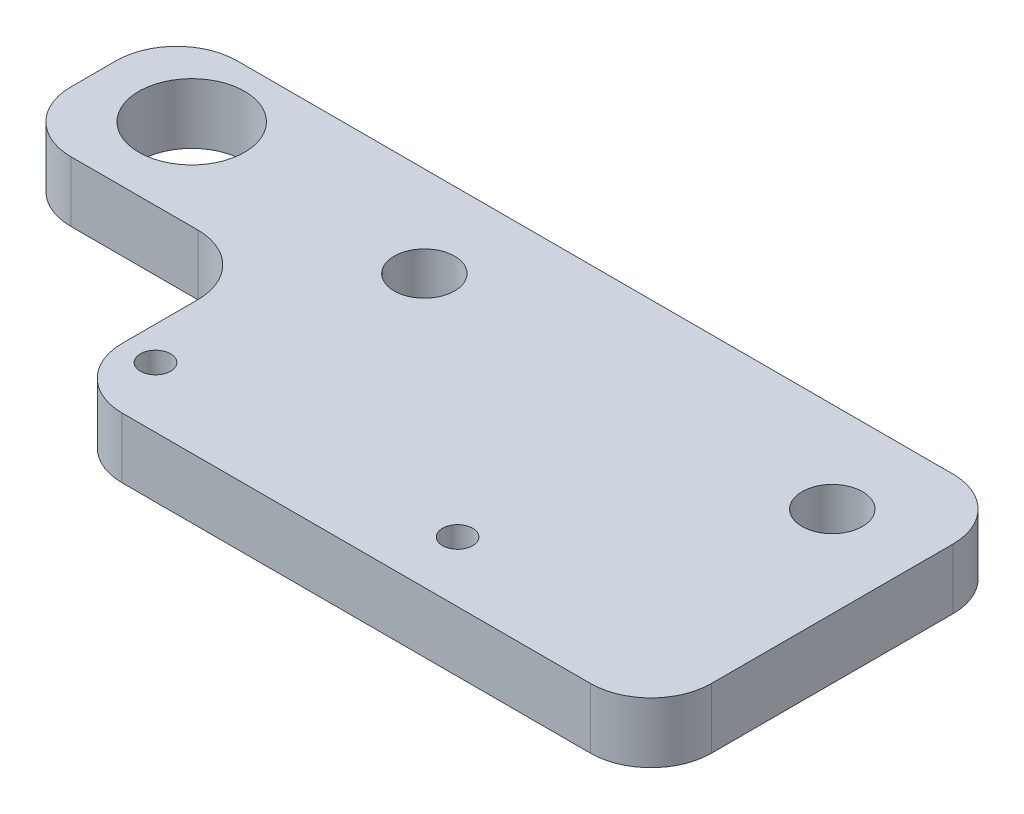
SolidWorks part; units mm, degrees
ref_plane "Front Plane" through (0, 0, 0) normal (0, 0, 1) x (1, 0, 0)
ref_plane "Top Plane" through (0, 0, 0) normal (0, 1, 0) x (1, 0, 0)
ref_plane "Right Plane" through (0, 0, 0) normal (1, 0, 0) x (0, 0, -1)
sketch "Sketch1" plane through (0, 0, 0) normal (0, 1, 0) x (1, 0, 0)
  line L0 (-11.7643, -8.8975) -> (-1.7643, -8.8975) construction
  line L5 (-12.8643, 1.1025) -> (6.6357, 1.1025)
  line L6 (-12.8643, -4.3975) -> (-12.8643, -10.8975)
  line L7 (-12.8643, -10.8975) -> (6.6357, -10.8975)
  line L8 (6.6357, 1.1025) -> (6.6357, -10.8975)
  line L10 (-12.8643, 1.1025) -> (-21.0643, 1.1025)
  line L12 (-12.8643, -4.3975) -> (-21.0643, -4.3975)
  line L13 (-21.0643, 1.1025) -> (-21.0643, -4.3975)
  circle A0 centre (-9.8643, -1.8975) radius 1
  circle A1 centre (3.6357, -1.8975) radius 1
  circle A2 centre (-6.7643, -5.8975) radius 8 construction
  circle A3 centre (-11.7643, -8.8975) radius 0.5
  circle A4 centre (-1.7643, -8.8975) radius 0.5
  circle A5 centre (-18.0643, -1.3975) radius 1.75
  point P14 (-6.7643, -8.8975)
  dimension "D1" = 2
  dimension "D2" = 2
  dimension "D4" = 16
  dimension "D7" = 3
  dimension "D8" = 3
  dimension "D10" = 3
  dimension "D12" = 1
  dimension "D13" = 1
  dimension "D16" = 8.2
  dimension "D18" = 3.5
  dimension "D3" = 13.5
  dimension "D5" = 10.4
  dimension "D6" = 4
  dimension "D9" = 3
  dimension "D11" = 5
  dimension "D14" = 10
  dimension "D15" = 3
  dimension "D17" = 0.5
  dimension "D19" = 3
  dimension "D20" = 3
extrude "Boss-Extrude1" add sketch "Sketch1" along normal blind 2
fillet "Fillet1" radius 2 6 edges at (6.6357, 1, -1.1025) (6.6357, 1, 10.8975) (-12.8643, 1, 10.8975) (-21.0643, 1, -1.1025) (-21.0643, 1, 4.3975) (-12.8643, 1, 4.3975)
